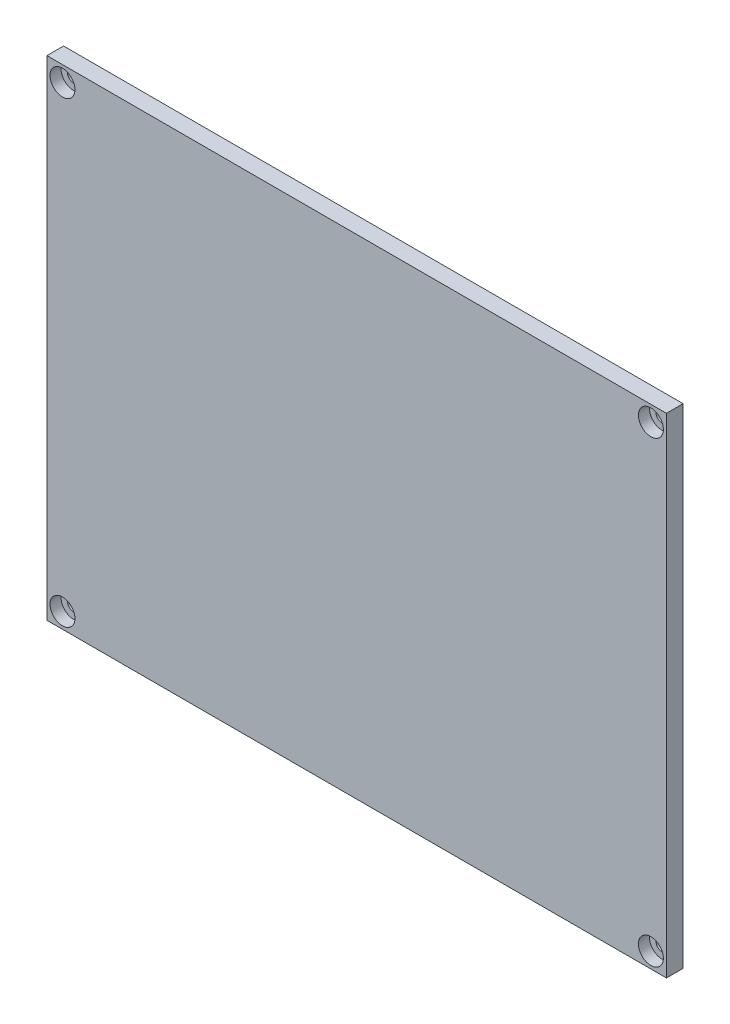
SolidWorks part; units mm, degrees
ref_plane "Front Plane" through (0, 0, 0) normal (0, 0, 1) x (1, 0, 0)
ref_plane "Top Plane" through (0, 0, 0) normal (0, 1, 0) x (1, 0, 0)
ref_plane "Right Plane" through (0, 0, 0) normal (1, 0, 0) x (0, 0, -1)
sketch "Sketch1" plane through (0, 0, 0) normal (0, 0, 1) x (1, 0, 0)
  line L1 (-56, -44.25) -> (56, -44.25)
  line L2 (-56, -44.25) -> (-56, 44.25)
  line L3 (-56, 44.25) -> (56, 44.25)
  line L4 (56, -44.25) -> (56, 44.25)
  line L5 (-56, -44.25) -> (56, 44.25) construction
  line L6 (-56, 44.25) -> (56, -44.25) construction
  point P0 (0, 0)
  dimension "D1" = 112
  dimension "D2" = 88.5
extrude "Boss-Extrude1" add sketch "Sketch1" along normal blind 3
sketch "Sketch2" plane through (0, 0, 3) normal (0, 0, 1) x (1, 0, 0)
  line L0 (-56, 44.25) -> (-56, -44.25) construction
  line L1 (-53, -41.25) -> (53, -41.25) construction
  line L2 (-53, -41.25) -> (-53, 41.25) construction
  line L3 (-53, 41.25) -> (53, 41.25) construction
  line L4 (53, -41.25) -> (53, 41.25) construction
  line L5 (-53, -41.25) -> (53, 41.25) construction
  line L6 (-53, 41.25) -> (53, -41.25) construction
  line L7 (56, 44.25) -> (-56, 44.25) construction
  circle A0 centre (-53, 41.25) radius 1.1
  circle A1 centre (53, 41.25) radius 1.1
  circle A2 centre (53, -41.25) radius 1.1
  circle A3 centre (-53, -41.25) radius 1.1
  point P0 (0, 0)
  dimension "D1" = 2.2
  dimension "D2" = 3
  dimension "D3" = 3
extrude "Cut-Extrude1" cut sketch "Sketch2" against normal through all
sketch "Sketch3" plane through (0, 0, 3) normal (0, 0, 1) x (1, 0, 0)
  line L1 (-56, -44.25) -> (56, -44.25)
  line L2 (-56, -44.25) -> (-56, 44.25)
  line L3 (-56, 44.25) -> (56, 44.25)
  line L4 (56, -44.25) -> (56, 44.25)
  line L5 (-56, -44.25) -> (56, 44.25) construction
  line L6 (-56, 44.25) -> (56, -44.25) construction
  line L7 (-55.8, -44.05) -> (55.8, -44.05)
  line L8 (-55.8, -44.05) -> (-55.8, 44.05)
  line L9 (-55.8, 44.05) -> (55.8, 44.05)
  line L10 (55.8, -44.05) -> (55.8, 44.05)
  line L11 (-55.8, -44.05) -> (55.8, 44.05) construction
  line L12 (-55.8, 44.05) -> (55.8, -44.05) construction
  point P0 (0, 0)
  point P7 (0, 0)
  dimension "D1" = 0.2
  dimension "D2" = 0.2
extrude "Cut-Extrude2" cut sketch "Sketch3" against normal through all
sketch "Sketch4" plane through (0, 0, 3) normal (0, 0, 1) x (1, 0, 0)
  circle A0 centre (-53, 41.25) radius 2.25
  circle A1 centre (53, 41.25) radius 2.25
  circle A2 centre (53, -41.25) radius 2.25
  circle A3 centre (-53, -41.25) radius 2.25
  dimension "D1" = 4.5
extrude "Cut-Extrude3" cut sketch "Sketch4" against normal blind 2
